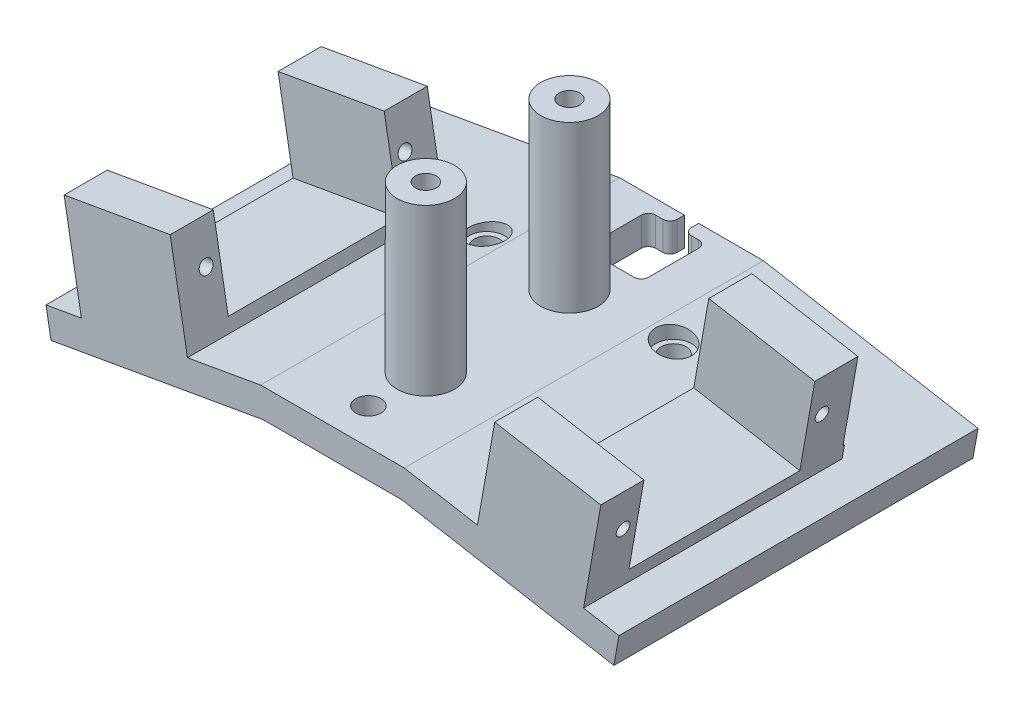
SolidWorks part; units mm, degrees
ref_plane "前视基准面" through (0, 0, 0) normal (0, 0, 1) x (1, 0, 0)
ref_plane "上视基准面" through (0, 0, 0) normal (0, 1, 0) x (1, 0, 0)
ref_plane "右视基准面" through (0, 0, 0) normal (1, 0, 0) x (0, 0, -1)
other "Configuration Table"
sketch "草图1" plane through (0, 0, 0) normal (0, 0, 1) x (1, 0, 0)
  line L0 (0, 0) -> (9.65, 0)
  line L1 (9.65, 0) -> (39.1943, -5.2094)
  line L2 (39.1943, -5.2094) -> (39.8889, -1.2702)
  line L3 (39.8889, -1.2702) -> (10, 4)
  line L4 (10, 4) -> (0, 4)
  line L5 (0, 4) -> (0, 0)
  dimension "D1" = 4
  dimension "D2" = 30
  dimension "D3" = 10
  dimension "D4" = 4
  dimension "D5" = 190
extrude "凸台-拉伸1" add sketch "草图1" along normal mid plane 50
sketch "草图2" plane through (0, 0, 25) normal (0, 0, 1) x (1, 0, 0)
  line L0 (20.1927, 2.2027) -> (20.514, 4.0246)
  line L1 (39.8889, -1.2702) -> (10, 4) construction
  line L2 (20.514, 4.0246) -> (35.2861, 1.4199)
  line L3 (35.2861, 1.4199) -> (34.9648, -0.402)
  line L4 (34.9648, -0.402) -> (20.1927, 2.2027)
  line L5 (39.1943, -5.2094) -> (39.8889, -1.2702) construction
  dimension "D1" = 1.85
  dimension "D2" = 20
  dimension "D3" = 15
extrude "凸台-拉伸2" add sketch "草图2" against normal blind 36
sketch "草图3" plane through (1.3068, 7.4114, 0) normal (0.1736, 0.9848, 0) x (0.9848, -0.1736, 0)
  line L0 (34.5034, 11) -> (34.5034, -25) construction
  line L1 (19.5034, -19) -> (34.5034, -19)
  line L2 (19.5034, -19) -> (19.5034, -25)
  line L3 (19.5034, -25) -> (34.5034, -25)
  line L4 (34.5034, -19) -> (34.5034, -25)
  line L5 (19.5034, 11) -> (19.5034, -25) construction
  line L6 (34.5034, 11) -> (34.5034, -25) construction
  line L7 (19.5034, 10.8) -> (34.5034, 10.8)
  line L8 (19.5034, 10.8) -> (19.5034, 4.8)
  line L9 (19.5034, 4.8) -> (34.5034, 4.8)
  line L10 (34.5034, 10.8) -> (34.5034, 4.8)
  line L11 (39.5034, -25) -> (34.5034, -25) construction
  dimension "D1" = 6
  dimension "D2" = 6
  dimension "D3" = 23.8
extrude "凸台-拉伸3" add sketch "草图3" along normal blind 12
sketch "草图4" plane through (33.9793, -5.9915, 0) normal (0.9848, -0.1736, 0) x (0, 0, -1)
  line L0 (4.8, 7.5257) -> (-19, 7.5257) construction
  line L1 (-19, 19.5257) -> (-19, 7.5257) construction
  line L2 (4.8, 19.5257) -> (4.8, 7.5257) construction
  circle A0 centre (-20.95, 14.0257) radius 0.95
  circle A1 centre (6.75, 14.0257) radius 0.95
  dimension "D1" = 6.5
  dimension "D2" = 6.5
  dimension "D3" = 1.95
  dimension "D4" = 1.95
  dimension "D5" = 1.9
  dimension "D6" = 1.9
extrude "切除-拉伸1" cut sketch "草图4" against normal blind 21
mirror "镜向1" about plane through (0, 0, 0) normal (1, 0, 0) of "切除-拉伸1", "凸台-拉伸3", "凸台-拉伸2", "凸台-拉伸1"
sketch "草图5" plane through (0, 4, 0) normal (0, 1, 0) x (1, 0, 0)
  circle A0 centre (0, -12) radius 4
  circle A1 centre (0, 8) radius 4
  circle A2 centre (0, 8) radius 1.45
  circle A3 centre (0, -12) radius 1.45
  dimension "D2" = 12
  dimension "D3" = 8
  dimension "D4" = 8
  dimension "D5" = 2.9
  dimension "D6" = 2.9
  dimension "D1" = 20
extrude "凸台-拉伸4" add sketch "草图5" along normal blind 23
sketch "草图6" plane through (0, 4, 0) normal (0, 1, 0) x (1, 0, 0)
  circle A0 centre (0, -20) radius 1.75
  circle A1 centre (-13, 9.5) radius 1.75
  circle A2 centre (13, 9.5) radius 1.75
  dimension "D1" = 20
  dimension "D2" = 26
  dimension "D3" = 29.5
  dimension "D4" = 3.5
  dimension "D5" = 13
extrude "切除-拉伸2" cut sketch "草图6" against normal blind 20
sketch "草图7" plane through (0, 4, 0) normal (0, 1, 0) x (1, 0, 0)
  circle A0 centre (-13, 9.5) radius 2.5
  circle A1 centre (13, 9.5) radius 2.5
  circle A2 centre (13, 9.5) radius 1.75 construction
  dimension "D1" = 5
extrude "切除-拉伸3" cut sketch "草图7" against normal blind 2
sketch "草图8" plane through (0, 4, 0) normal (0, 1, 0) x (1, 0, 0)
  line L0 (10, 25) -> (-10, 25) construction
  line L1 (-4, 23) -> (-1, 23)
  line L2 (-4, 23) -> (-4, 14)
  line L3 (-4, 14) -> (4, 14)
  line L4 (4, 23) -> (4, 14)
  line L5 (-4, 23) -> (4, 14) construction
  line L6 (-4, 14) -> (4, 23) construction
  line L7 (-1, 25) -> (1, 25)
  line L8 (-1, 25) -> (-1, 23)
  line L10 (1, 25) -> (1, 23)
  line L11 (1, 23) -> (4, 23)
  point P0 (0, 18.5)
  point P12 (0, 25)
  dimension "D1" = 8
  dimension "D2" = 9
  dimension "D3" = 14
  dimension "D4" = 2
extrude "切除-拉伸4" cut sketch "草图8" against normal through all
fillet "圆角4" radius 1 6 edges at (4, 2, -23) (-4, 2, -23) (1, 2, -23) (-1, 2, -23) (-4, 2, -14) (4, 2, -14)
